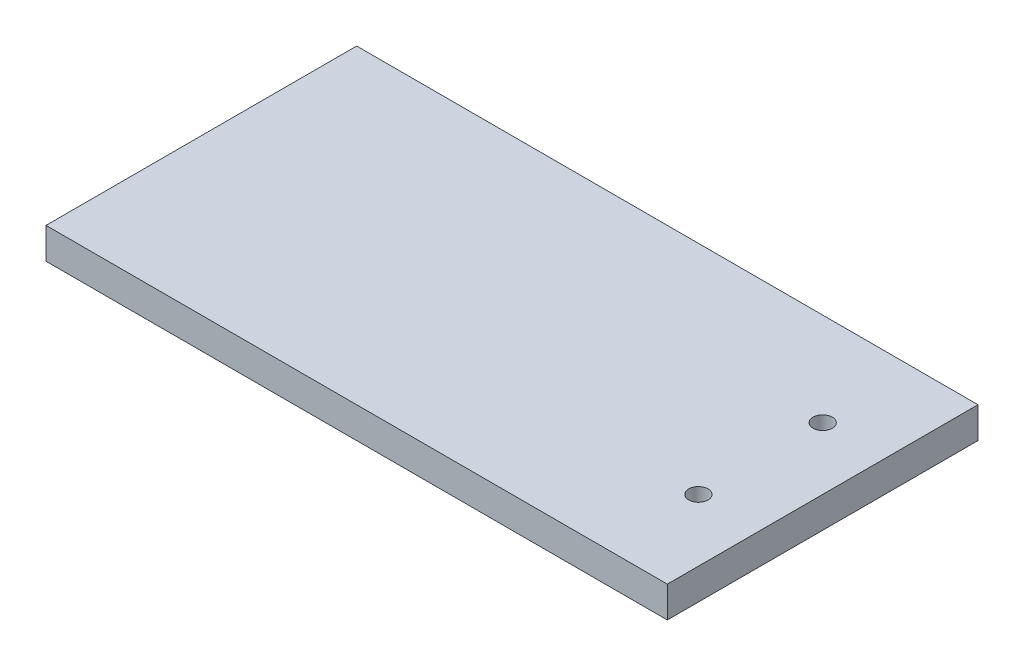
SolidWorks part; units mm, degrees
material "Alliage 1060"
ref_plane "Front" through (0, 0, 0) normal (0, 0, 1) x (1, 0, 0)
ref_plane "Top" through (0, 0, 0) normal (0, 1, 0) x (1, 0, 0)
ref_plane "Right" through (0, 0, 0) normal (1, 0, 0) x (0, 0, -1)
sketch "Esquisse1" plane through (0, 0, 0) normal (0, 1, 0) x (1, 0, 0)
  line L1 (-100, 50) -> (100, 50)
  line L2 (-100, 50) -> (-100, -50)
  line L3 (-100, -50) -> (100, -50)
  line L4 (100, 50) -> (100, -50)
  line L5 (-100, 50) -> (100, -50) construction
  line L6 (-100, -50) -> (100, 50) construction
  point P0 (0, 0)
  dimension "D1" = 100
  dimension "D2" = 200
extrude "Boss.-Extru.1" add sketch "Esquisse1" along normal blind 10
hole_wizard "Fraisage pour vis à tête fraisée M61" positions "Esquisse2" profile "Esquisse3" countersink size "M6" standard "ISO" end condition through all
sketch "Esquisse2" plane through (0, 0, 0) normal (0, -1, 0) x (-1, 0, 0)
  line L1 (0, 0) -> (-100, 0) construction
  line L2 (-100, -50) -> (-100, 50) construction
  line L4 (-80, 20) -> (-80, -20) construction
  point P0 (-80, 20)
  point P2 (-80, -20)
  point P16 (-80, 0)
  dimension "D1" = 40
  dimension "D2" = 20
sketch "Esquisse3" plane through (80, 0, -20) normal (1, 0, 0) x (0, 0, -1)
  line L0 (0, 0) -> (0, 10)
  line L1 (0, 10) -> (3.1, 10)
  line L2 (3.1, 10) -> (3.1, 3.2)
  line L3 (3.1, 3.2) -> (6.3, 0)
  line L5 (6.3, 0) -> (0, 0)
  line L6 (-3.1, 3.2) -> (-6.3, 0) construction
  line L11 (0, -6.35) -> (0, 107.95) construction
  dimension "Diamètre du perçage jusqu'au prochain" = 6.2
  dimension "Profondeur du perçage jusqu'au prochain" = 10
  dimension "Diamètre du fraisage entrant" = 12.6
  dimension "Angle du fraisage entrant" = 90
